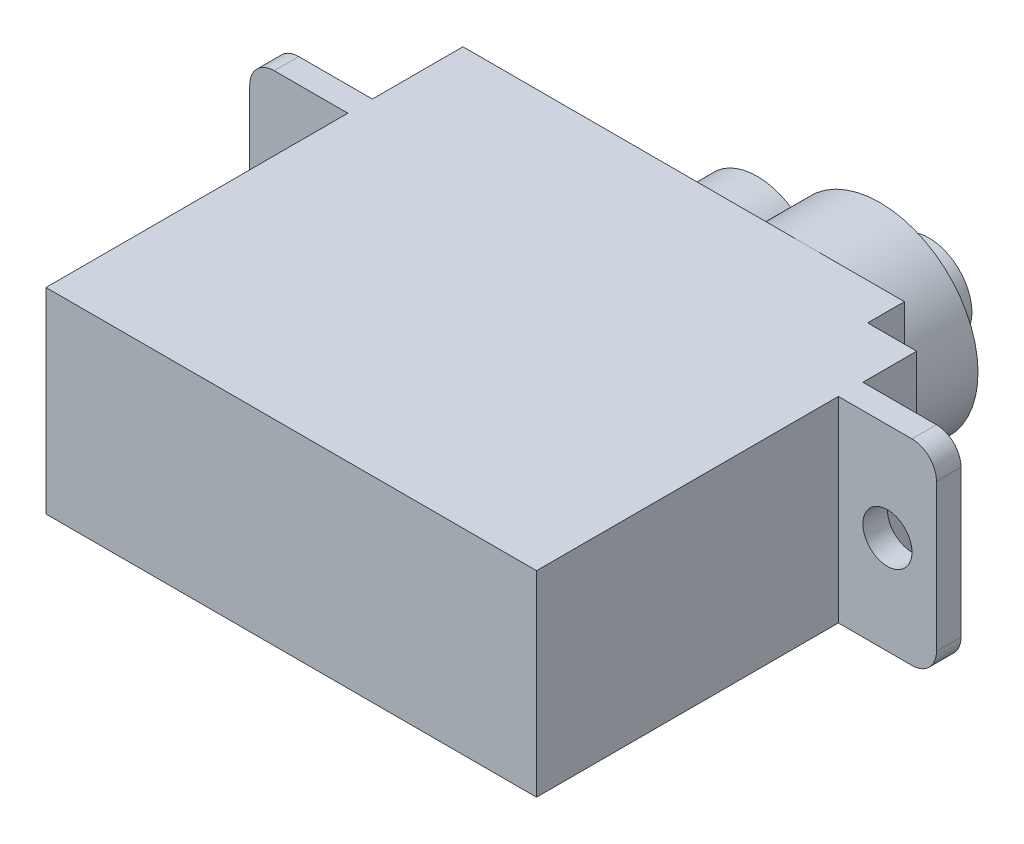
SolidWorks part; units mm, degrees
ref_plane "Front Plane" through (0, 0, 0) normal (0, 0, 1) x (1, 0, 0)
ref_plane "Top Plane" through (0, 0, 0) normal (0, 1, 0) x (1, 0, 0)
ref_plane "Right Plane" through (0, 0, 0) normal (1, 0, 0) x (0, 0, -1)
sketch "Sketch1" plane through (0, 0, 0) normal (0, 1, 0) x (1, 0, 0)
  line L0 (-8.0488, 5.8014) -> (-8.0488, -11.1986)
  line L1 (-8.0488, -11.1986) -> (11.9512, -11.1986)
  line L2 (11.9512, -11.1986) -> (11.9512, 4.3014)
  line L3 (11.9512, 4.3014) -> (9.9512, 4.3014)
  line L4 (9.9512, 4.3014) -> (9.9512, 5.8014)
  line L5 (9.9512, 5.8014) -> (-8.0488, 5.8014)
  line L6 (-8.0488, 2.108) -> (-12.0488, 2.108)
  line L7 (-12.0488, 2.108) -> (-12.0488, 1.108)
  line L8 (-12.0488, 1.108) -> (-8.0488, 1.108)
  line L9 (11.9512, 2.108) -> (15.9512, 2.108)
  line L10 (15.9512, 2.108) -> (15.9512, 1.108)
  line L11 (15.9512, 1.108) -> (11.9512, 1.108)
  line L12 (-8.0488, 1.108) -> (-8.0488, 2.108)
  line L13 (11.9512, 2.108) -> (11.9512, 1.108)
  dimension "D1" = 20
  dimension "D2" = 17
  dimension "D3" = 1.5
  dimension "D4" = 2
  dimension "D5" = 4
  dimension "D6" = 1
  dimension "D7" = 4
  dimension "D8" = 1
extrude "Boss-Extrude3" add sketch "Sketch1" along normal blind 8 contours L4 L5 L0 L1 L2 L3 | L11 L10 L9 L2 | L6 L7 L8 L12
sketch "Sketch2" plane through (0, 0, -5.8014) normal (0, 0, -1) x (-1, 0, 0)
  line L0 (-9.9512, 8) -> (-9.9512, 0) construction
  line L1 (-9.9512, 8) -> (8.0488, 8) construction
  circle A0 centre (-5.9512, 4) radius 4
  dimension "D2" = 8
  dimension "D1" = 4
  dimension "D3" = 4
extrude "Boss-Extrude5" add sketch "Sketch2" along normal blind 3
sketch "Sketch3" plane through (0, 0, -5.8014) normal (0, 0, -1) x (-1, 0, 0)
  circle A0 centre (-0.9512, 3.9258) radius 2.5
  circle A1 centre (-5.9512, 4) radius 4 construction
  dimension "D1" = 5
  dimension "D2" = 5
extrude "Boss-Extrude6" add sketch "Sketch3" along normal blind 3
sketch "Sketch4" plane through (0, 0, -2.108) normal (0, 0, -1) x (-1, 0, 0)
  line L0 (-11.9512, 8) -> (-15.9512, 8) construction
  line L1 (-15.9512, 8) -> (-15.9512, 0) construction
  line L2 (8.0488, 0) -> (12.0488, 0) construction
  line L3 (12.0488, 8) -> (12.0488, 0) construction
  circle A0 centre (-13.9512, 4) radius 1
  circle A1 centre (10.0488, 4) radius 1
  dimension "D3" = 2
  dimension "D4" = 2
  dimension "D1" = 4
  dimension "D2" = 2
  dimension "D5" = 4
  dimension "D6" = 2
extrude "Cut-Extrude1" cut sketch "Sketch4" against normal through all
fillet "Fillet2" radius 1 1 edges at (15.9512, 8, -1.608)
fillet "Fillet3" radius 1 3 edges at (-12.0488, 0, -1.608) (-12.0488, 8, -1.608) (15.9512, 0, -1.608)
sketch "Sketch6" plane through (0, 0, -8.8014) normal (0, 0, -1) x (-1, 0, 0)
  circle A0 centre (-5.9512, 4) radius 1.75
  dimension "D1" = 3.5
extrude "Boss-Extrude8" add sketch "Sketch6" along normal blind 2
